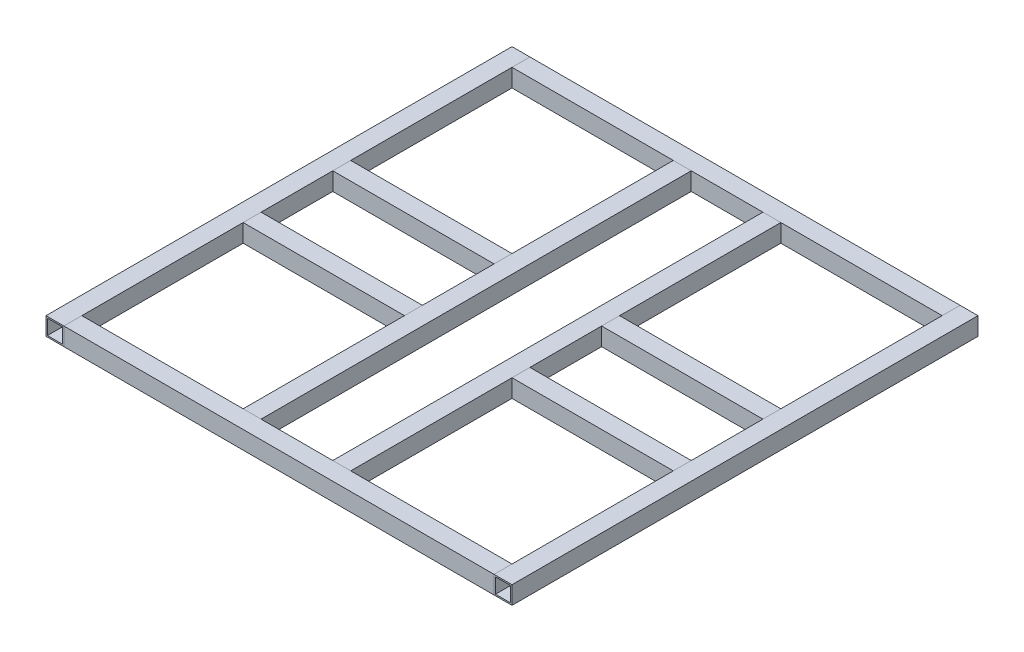
SolidWorks part; units mm, degrees
ref_plane "Front Plane" through (0, 0, 0) normal (0, 0, 1) x (1, 0, 0)
ref_plane "Top Plane" through (0, 0, 0) normal (0, 1, 0) x (1, 0, 0)
ref_plane "Right Plane" through (0, 0, 0) normal (1, 0, 0) x (0, 0, -1)
sketch "Sketch1" plane through (0, 0, 0) normal (0, 1, 0) x (1, 0, 0)
  line L0 (-25, 125) -> (-25, -125)
  line L1 (-125, 125) -> (125, 125)
  line L2 (-125, 125) -> (-125, -125)
  line L3 (-125, -125) -> (125, -125)
  line L4 (125, 125) -> (125, -125)
  line L5 (-125, 125) -> (125, -125) construction
  line L6 (-125, -125) -> (125, 125) construction
  line L7 (25, 125) -> (25, -125)
  line L8 (-125, 25) -> (-25, 25)
  line L9 (25, 25) -> (125, 25)
  line L10 (25, -25) -> (125, -25)
  line L11 (-25, -25) -> (-125, -25)
  point P0 (0, 0)
  dimension "D1" = 250
  dimension "D2" = 100
  dimension "D3" = 100
  dimension "D4" = 100
  dimension "D5" = 100
other "Inox vuông - configured 10X0.8(1)"
ref_plane "Plane1" through (-125, 0, -125) normal (0, 0, 1) x (1, 0, 0)
sketch "Sketch11" plane through (-125, 0, -125) normal (0, 0, 1) x (1, 0, 0)
  line L0 (-4.2, 4.2) -> (4.2, 4.2)
  line L1 (-5, 5) -> (5, 5)
  line L2 (-5, 5) -> (-5, -5)
  line L3 (-5, -5) -> (5, -5)
  line L4 (5, 5) -> (5, -5)
  line L5 (-5, 5) -> (5, -5) construction
  line L6 (-5, -5) -> (5, 5) construction
  line L7 (4.2, 4.2) -> (4.2, -4.2)
  line L8 (-4.2, -4.2) -> (4.2, -4.2)
  line L9 (-4.2, 4.2) -> (-4.2, -4.2)
  point P0 (0, 0)
  point P10 (0, 5)
  point P11 (-5, 0)
  point P12 (5, 0)
  point P13 (0, -5)
  point P14 (0, 0)
  dimension "D1" = 10
  dimension "D2" = 0.8
